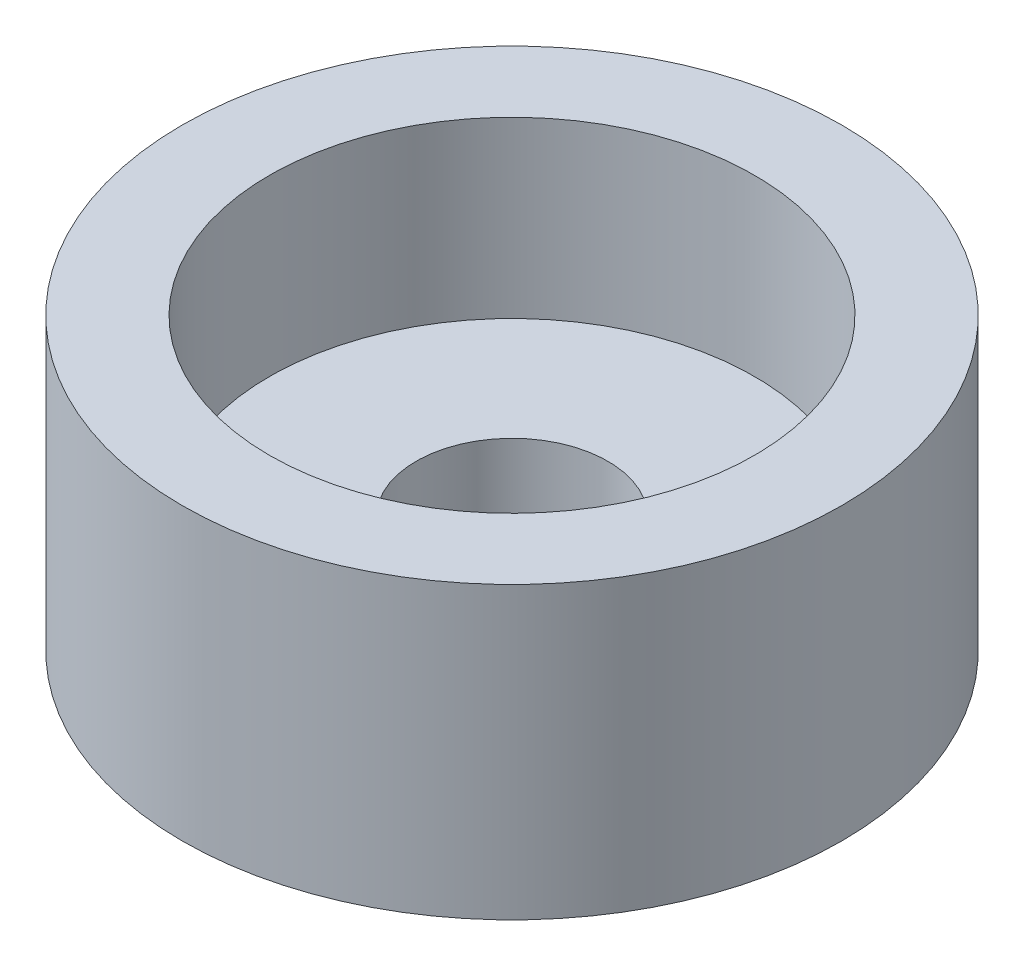
SolidWorks part; units mm, degrees
ref_plane "Plano frontal" through (0, 0, 0) normal (0, 0, 1) x (1, 0, 0)
ref_plane "Plano superior" through (0, 0, 0) normal (0, 1, 0) x (1, 0, 0)
ref_plane "Plano direito" through (0, 0, 0) normal (1, 0, 0) x (0, 0, -1)
sketch "Esboço1" plane through (0, 0, 0) normal (0, 1, 0) x (1, 0, 0)
  circle A0 centre (0, 0) radius 4.175 construction
  circle A1 centre (0, 0) radius 1.65
  circle A2 centre (0, 0) radius 5.675
  dimension "D1" = 8.35
  dimension "D2" = 3.3
  dimension "D3" = 1.5
extrude "Ressalto-extrusão1" add sketch "Esboço1" along normal blind 2
sketch "Esboço2" plane through (0, 2, 0) normal (0, 1, 0) x (1, 0, 0)
  circle A0 centre (0, 0) radius 4.175
  circle A1 centre (0, 0) radius 5.675 construction
  circle A2 centre (0, 0) radius 5.675
  dimension "D1" = 8.35
extrude "Ressalto-extrusão2" add sketch "Esboço2" along normal blind 3
